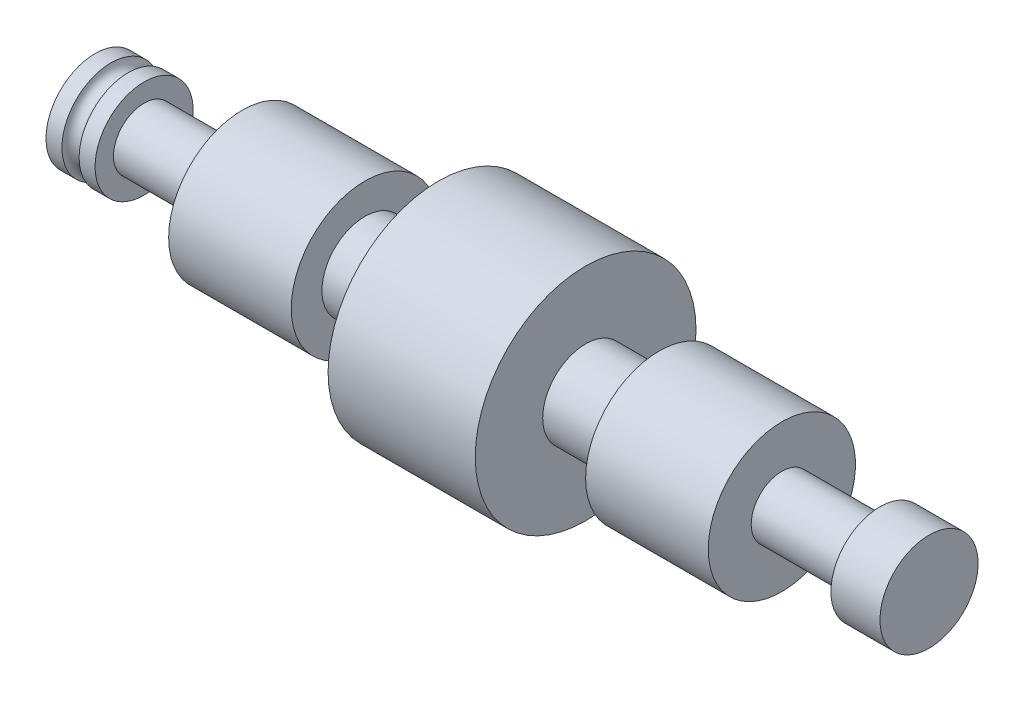
SolidWorks part; units mm, degrees
ref_plane "Front Plane" through (0, 0, 0) normal (0, 0, 1) x (1, 0, 0)
ref_plane "Top Plane" through (0, 0, 0) normal (0, 1, 0) x (1, 0, 0)
ref_plane "Right Plane" through (0, 0, 0) normal (1, 0, 0) x (0, 0, -1)
sketch "Sketch1" plane through (0, 0, 0) normal (0, 0, 1) x (1, 0, 0)
  line L0 (-170, 0) -> (-170, 20)
  line L1 (-170, 20) -> (-150, 20)
  line L2 (-150, 20) -> (-150, 12.5)
  line L3 (-150, 12.5) -> (-110, 12.5)
  line L4 (-110, 12.5) -> (-110, 30)
  line L5 (-110, 30) -> (-60, 30)
  line L6 (-60, 30) -> (-60, 17.5)
  line L7 (-30, 17.5) -> (-30, 45)
  line L8 (-30, 45) -> (0, 45)
  line L9 (0, 45) -> (0, 0)
  line L10 (0, 0) -> (-170, 0)
  line L11 (-60, 17.5) -> (-30, 17.5)
  line L12 (-99.1444, 0) -> (107.7005, 0) construction
  dimension "D1" = 40
  dimension "D2" = 25
  dimension "D3" = 60
  dimension "D4" = 35
  dimension "D5" = 90
  dimension "D6" = 20
  dimension "D7" = 40
  dimension "D8" = 50
  dimension "D9" = 30
  dimension "D10" = 30
revolve "Revolve1" add sketch "Sketch1" angle 360 about L12
sketch "Sketch2" plane through (0, 0, 0) normal (0, 0, 1) x (1, 0, 0)
  line L0 (-60, 30) -> (-110, 30) construction
  line L1 (-90, 35) -> (-80, 35)
  line L2 (-90, 35) -> (-90, 25)
  line L3 (-90, 25) -> (-80, 25)
  line L4 (-80, 35) -> (-80, 25)
  line L5 (-90, 35) -> (-80, 25) construction
  line L6 (-90, 25) -> (-80, 35) construction
  line L7 (-170, 0) -> (11.8982, 0) construction
  line L8 (-170, 20) -> (-170, -20) construction
  circle A0 centre (-160, 20.1216) radius 3.5
  point P2 (-85, 30)
  point P14 (0, 0)
  point P15 (0, 0)
  dimension "D1" = 7
  dimension "D2" = 10
  dimension "D3" = 10
  dimension "D4" = 160
  dimension "D5" = 85
revolve "Cut-Revolve1" cut sketch "Sketch2" angle 360 about L7
mirror "Mirror1" about plane through (0, 0, 0) normal (1, 0, 0) of "Revolve1"
